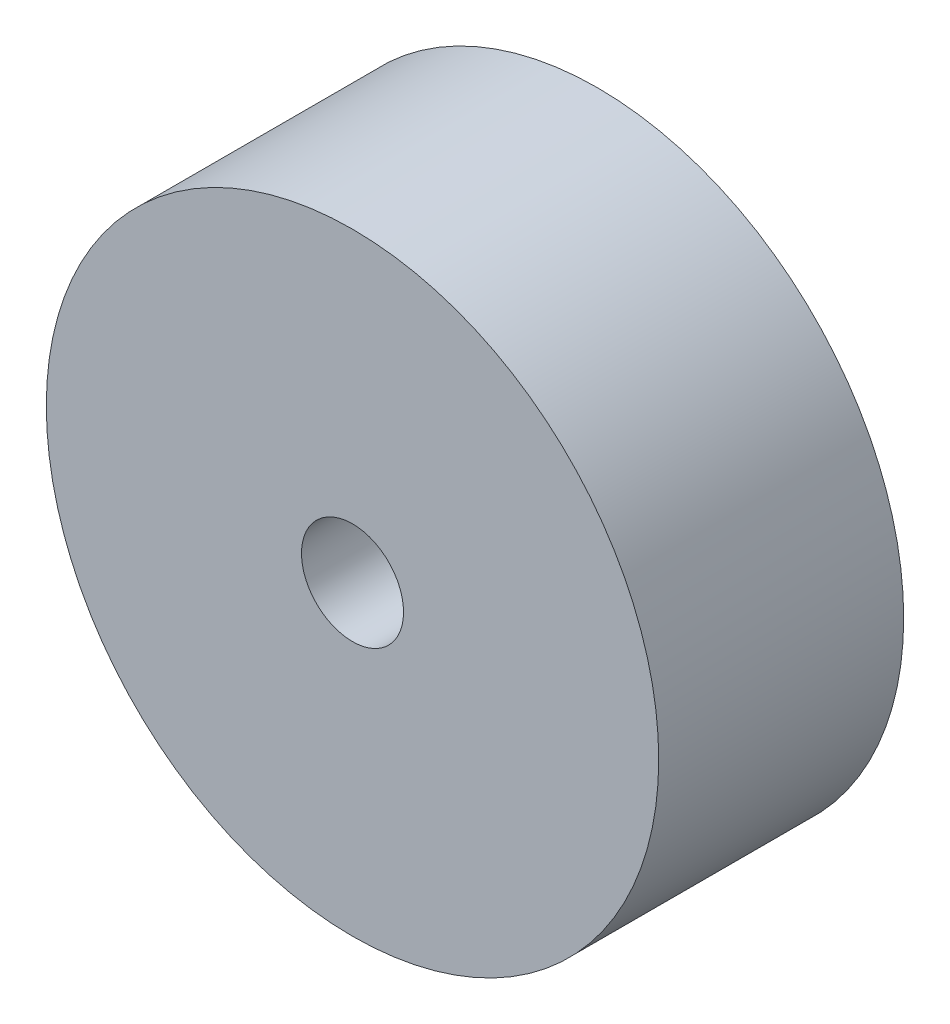
SolidWorks part; units mm, degrees
material "自訂玻璃纖維"
ref_plane "前基準面" through (0, 0, 0) normal (0, 0, 1) x (1, 0, 0)
ref_plane "上基準面" through (0, 0, 0) normal (0, 1, 0) x (1, 0, 0)
ref_plane "右基準面" through (0, 0, 0) normal (1, 0, 0) x (0, 0, -1)
sketch "草圖1" plane through (0, 0, 0) normal (0, 0, 1) x (1, 0, 0)
  circle A0 centre (-13.9029, 4.6452) radius 7.5
  circle A1 centre (-13.9029, 4.6452) radius 1.25
  point P13 (-13.9029, 4.6452)
  dimension "D1" = 15
  dimension "D2" = 2.5
extrude "填料-伸長1" add sketch "草圖1" along normal blind 6
